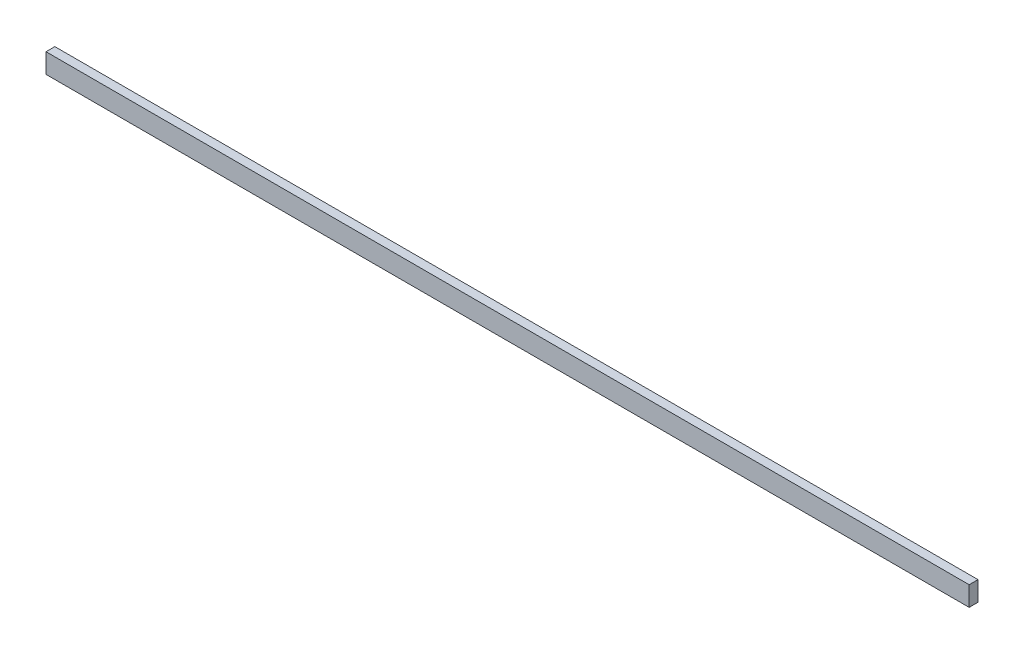
SolidWorks part; units mm, degrees
ref_plane "Front Plane" through (0, 0, 0) normal (0, 0, 1) x (1, 0, 0)
ref_plane "Top Plane" through (0, 0, 0) normal (0, 1, 0) x (1, 0, 0)
ref_plane "Right Plane" through (0, 0, 0) normal (1, 0, 0) x (0, 0, -1)
sketch "Sketch1" plane through (0, 0, 0) normal (0, 0, 1) x (1, 0, 0)
  line L1 (-940, -20) -> (940, -20)
  line L2 (-940, -20) -> (-940, 20)
  line L3 (-940, 20) -> (940, 20)
  line L4 (940, -20) -> (940, 20)
  line L5 (-940, -20) -> (940, 20) construction
  line L6 (-940, 20) -> (940, -20) construction
  point P0 (0, 0)
  dimension "D1" = 1880
  dimension "D2" = 40
extrude "Boss-Extrude1" add sketch "Sketch1" along normal blind 10 and the other way blind 8
